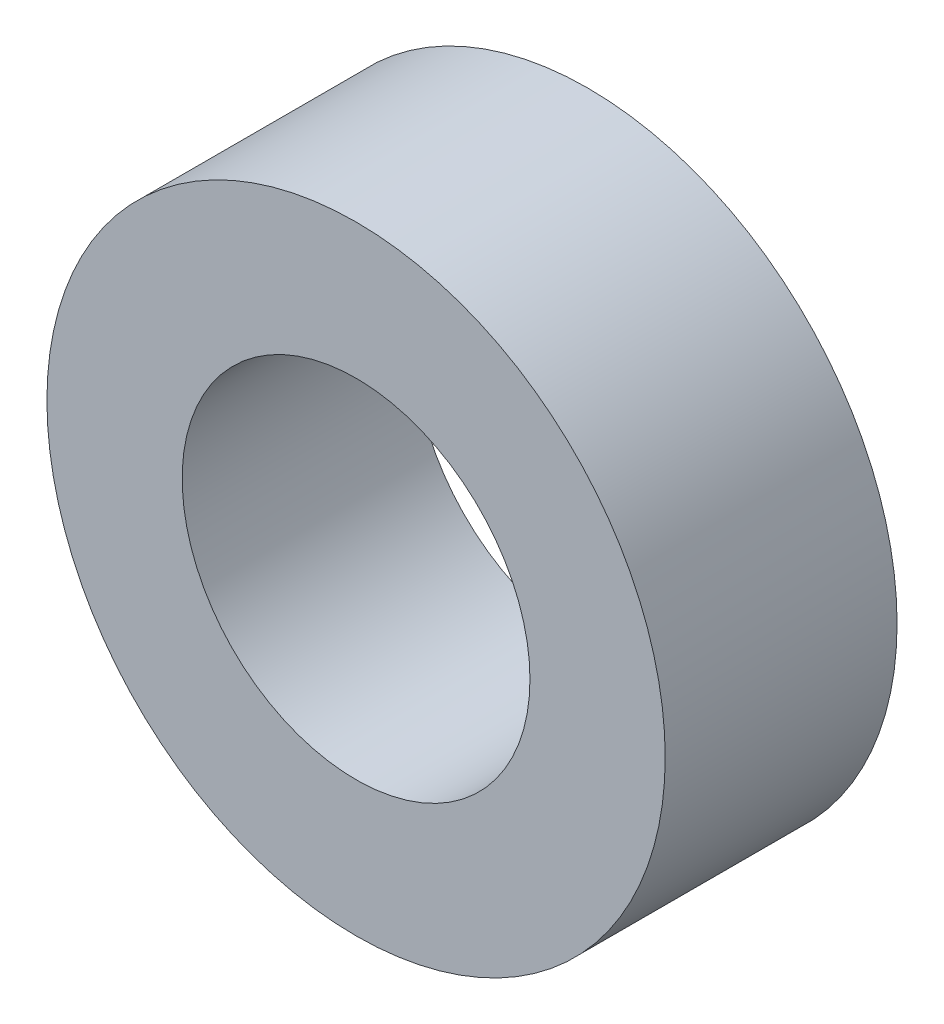
SolidWorks part; units mm, degrees
ref_plane "Plano frontal" through (0, 0, 0) normal (0, 0, 1) x (1, 0, 0)
ref_plane "Plano superior" through (0, 0, 0) normal (0, 1, 0) x (1, 0, 0)
ref_plane "Plano direito" through (0, 0, 0) normal (1, 0, 0) x (0, 0, -1)
sketch "Esboço1" plane through (0, 0, 0) normal (0, 0, 1) x (1, 0, 0)
  circle A0 centre (0, 0) radius 4
  circle A1 centre (0, 0) radius 2.25
  dimension "D1" = 4.5
  dimension "D2" = 8
extrude "Ressalto-extrusão1" add sketch "Esboço1" along normal blind 3
